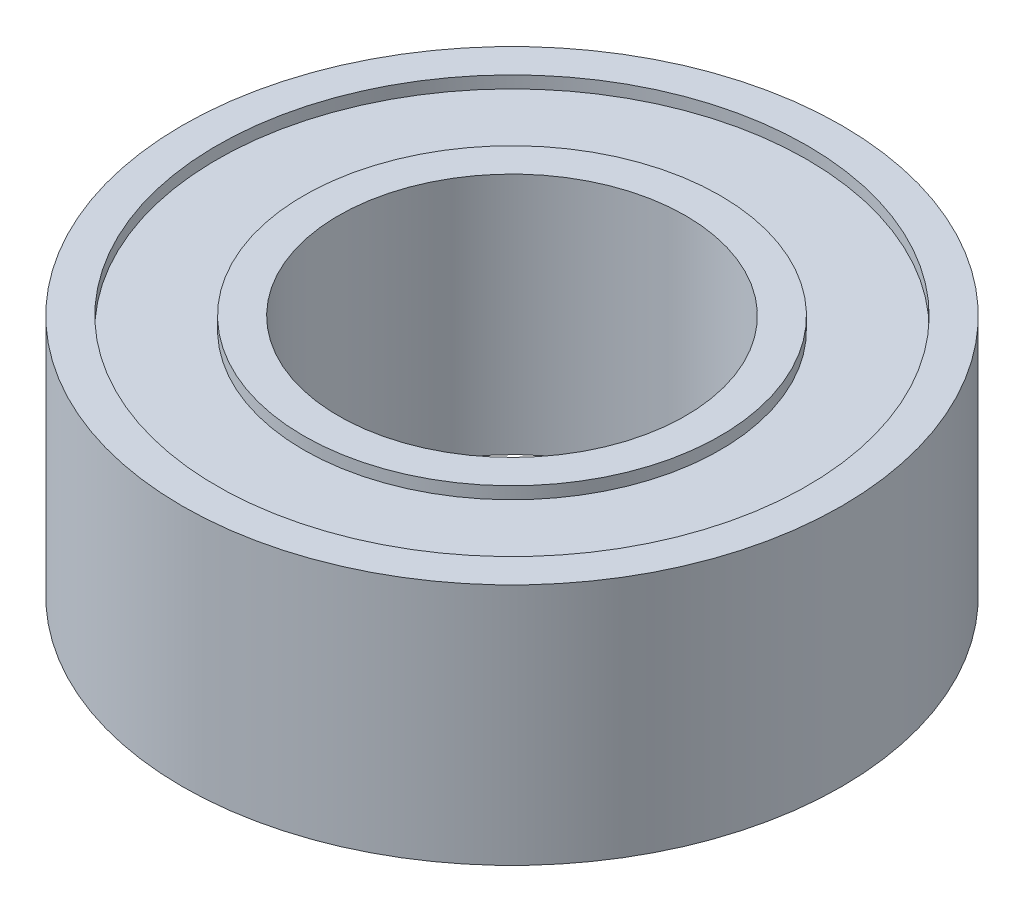
SolidWorks part; units mm, degrees
material "AISI 304"
ref_plane "前视基准面" through (0, 0, 0) normal (0, 0, 1) x (1, 0, 0)
ref_plane "上视基准面" through (0, 0, 0) normal (0, 1, 0) x (1, 0, 0)
ref_plane "右视基准面" through (0, 0, 0) normal (1, 0, 0) x (0, 0, -1)
other "Configuration Table"
sketch "草图2" plane through (0, 0, 0) normal (0, 0, 1) x (1, 0, 0)
  line L0 (0, 0) -> (0, 0.8612) construction
  line L1 (0, 0) -> (1.8966, 0) construction
  line L2 (5, 3.5) -> (5, -3.5)
  line L3 (5, 3.5) -> (6, 3.5)
  line L4 (6, 3.5) -> (6, 3.15)
  line L5 (6, 3.15) -> (8.5, 3.15)
  line L6 (8.5, 3.15) -> (8.5, 3.5)
  line L7 (8.5, 3.5) -> (9.5, 3.5)
  line L8 (9.5, 3.5) -> (9.5, -3.5)
  line L9 (8.5, -3.5) -> (9.5, -3.5)
  line L10 (8.5, -3.15) -> (8.5, -3.5)
  line L11 (6, -3.15) -> (8.5, -3.15)
  line L12 (6, -3.5) -> (6, -3.15)
  line L13 (5, -3.5) -> (6, -3.5)
  point P15 (9.5, 0)
  point P20 (5, 0)
  dimension "D1" = 7
  dimension "D2" = 10
  dimension "D3" = 19
  dimension "D4" = 1
  dimension "D5" = 0.35
revolve "旋转1" add sketch "草图2" angle 360 about L0
equation "\"内径\" = 10"
equation "\"外径\" = 19"
equation "\"D1@草图2\" = \"厚\""
equation "\"D2@草图2\"=\"内径\""
equation "\"D3@草图2\"=\"外径\""
equation "\"D4@草图2\"=(\"外径\"-\"内径\")/9"
equation "\"D5@草图2\"= \"厚\" / 20"
equation "\"厚\"= 7"
